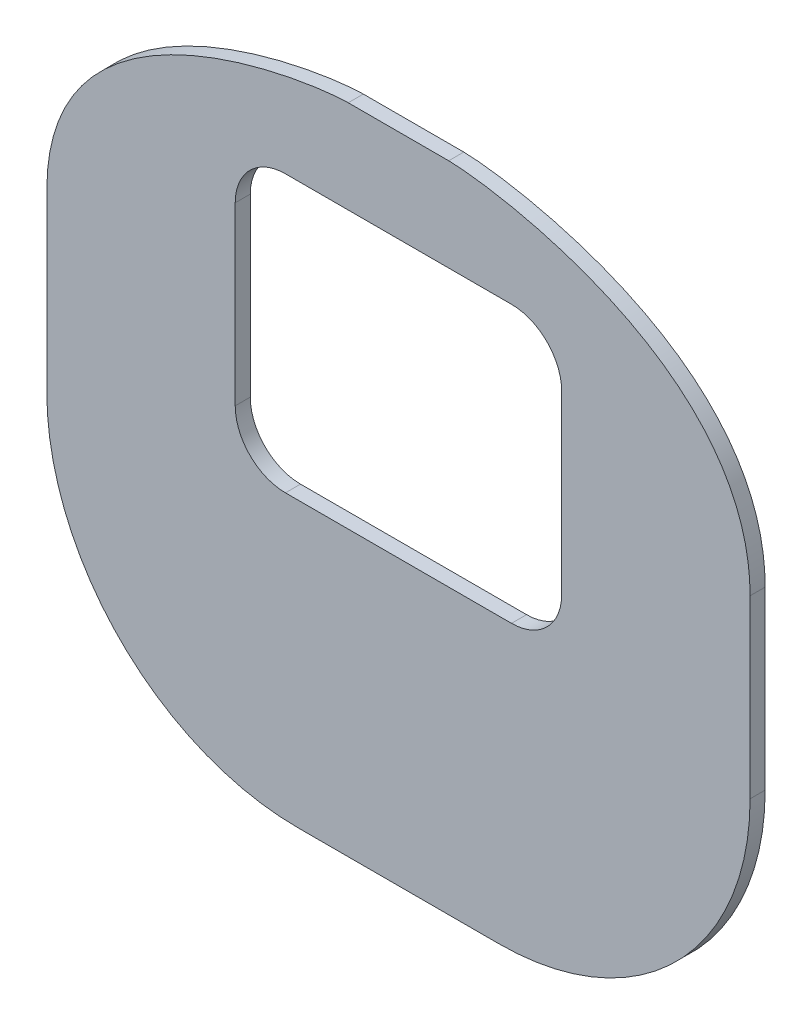
SolidWorks part; units mm, degrees
ref_plane "Front Plane" through (0, 0, 0) normal (0, 0, 1) x (1, 0, 0)
ref_plane "Top Plane" through (0, 0, 0) normal (0, 1, 0) x (1, 0, 0)
ref_plane "Right Plane" through (0, 0, 0) normal (1, 0, 0) x (0, 0, -1)
sketch "Sketch1" plane through (0, 0, 0) normal (0, 0, 1) x (1, 0, 0)
  line L0 (0, 33.5) -> (0, -96.5) construction
  line L1 (-70, 33.5) -> (70, 33.5) construction
  line L2 (-70, 33.5) -> (-70, -96.5) construction
  line L3 (-70, -96.5) -> (70, -96.5) construction
  line L4 (70, 33.5) -> (70, -96.5) construction
  line L5 (-25, 33.5) -> (25, 33.5) construction
  line L6 (-20, -96.5) -> (20, -96.5) construction
  line L7 (-70, -11.5) -> (70, -11.5) construction
  line L8 (-70, -11.5) -> (-70, -46.5)
  line L9 (-70, -46.5) -> (70, -46.5) construction
  line L10 (70, -11.5) -> (70, -46.5)
  line L11 (-10, 33.5) -> (10, 33.5)
  line L12 (20.2739, -96.5) -> (21.2739, -96.5)
  line L13 (-20, -96.5) -> (20.2739, -96.5)
  line L14 (21.2739, -96.5) -> (20, -96.5)
  line L15 (-70, -11.5) -> (-70, 26.5) construction
  line L16 (-70, 26.5) -> (-18, 33.5) construction
  line L17 (-18, 33.5) -> (-10, 33.5) construction
  line L18 (10, 33.5) -> (18, 33.5) construction
  line L19 (18, 33.5) -> (70, 26.5) construction
  line L20 (70, 26.5) -> (70, -11.5) construction
  line L21 (55, 0) -> (-55, 0) construction
  arc A0 (-70, -11.5) -> (-25, 33.5) centre (-25, -11.5) cw construction
  arc A1 (25, 33.5) -> (70, -11.5) centre (25, -11.5) cw construction
  arc A2 (-70, -46.5) -> (-20, -96.5) centre (-20, -46.5) ccw
  arc A3 (20, -96.5) -> (70, -46.5) centre (20, -46.5) ccw
  spline S0 degree 3 poles (-70, -11.5) (-70, 26.5) (-18, 33.5) (-10, 33.5) knots 0 0 0 0 1 1 1 1
  spline S1 degree 3 poles (10, 33.5) (18, 33.5) (70, 26.5) (70, -11.5) knots 0 0 0 0 1 1 1 1
  point P10 (0, 33.5)
  point P19 (0, -96.5)
  point P24 (0, 33.5)
  dimension "D3" = 50
  dimension "D1" = 130
  dimension "D2" = 140
  dimension "D4" = 20
  dimension "D5" = 45
  dimension "D6" = 38
  dimension "D7" = 52
  dimension "D8" = 52
  dimension "D9" = 38
  dimension "D10" = 33.5
extrude "Boss-Extrude1" add sketch "Sketch1" along normal blind 3 contours S1 L11 S0 L8 A2 L13 A3 L10
sketch "Sketch2" plane through (0, 0, 3) normal (0, 0, 1) x (1, 0, 0)
  line L0 (0, -1.65) -> (0, 1.65) construction
  line L1 (-22.5, -40) -> (22.5, -40)
  line L2 (-32.5, -30) -> (-32.5, 5)
  line L3 (-22.5, 15) -> (22.5, 15)
  line L4 (32.5, -30) -> (32.5, 5)
  line L5 (-32.5, -40) -> (32.5, 15) construction
  line L6 (-32.5, 15) -> (32.5, -40) construction
  line L9 (1.65, 0) -> (-1.65, 0) construction
  arc A0 (-22.5, -40) -> (-32.5, -30) centre (-22.5, -30) cw
  arc A1 (22.5, -40) -> (32.5, -30) centre (22.5, -30) ccw
  arc A2 (22.5, 15) -> (32.5, 5) centre (22.5, 5) cw
  arc A3 (-32.5, 5) -> (-22.5, 15) centre (-22.5, 5) cw
  point P0 (0, -12.5)
  dimension "D3" = 10
  dimension "D1" = 55
  dimension "D2" = 65
  dimension "D4" = 40
extrude "Cut-Extrude1" cut sketch "Sketch2" against normal blind 10
